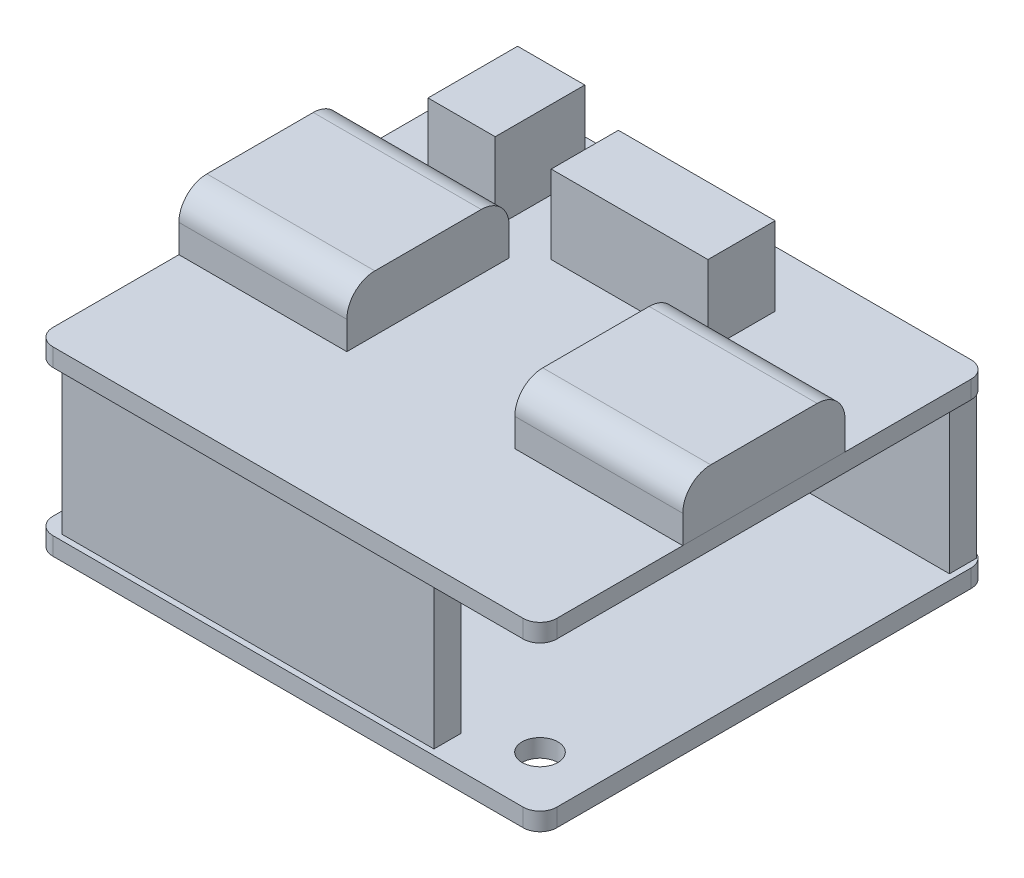
SolidWorks part; units mm, degrees
ref_plane "Front Plane" through (0, 0, 0) normal (0, 0, 1) x (1, 0, 0)
ref_plane "Top Plane" through (0, 0, 0) normal (0, 1, 0) x (1, 0, 0)
ref_plane "Right Plane" through (0, 0, 0) normal (1, 0, 0) x (0, 0, -1)
sketch "Sketch1" plane through (0, 0, 0) normal (0, 1, 0) x (1, 0, 0)
  line L1 (-22.5, -20) -> (22.5, -20)
  line L2 (-22.5, -20) -> (-22.5, 20)
  line L3 (-22.5, 20) -> (22.5, 20)
  line L4 (22.5, -20) -> (22.5, 20)
  line L5 (-22.5, -20) -> (22.5, 20) construction
  line L6 (-22.5, 20) -> (22.5, -20) construction
  point P0 (0, 0)
  dimension "D1" = 45
  dimension "D2" = 40
extrude "Boss-Extrude1" add sketch "Sketch1" along normal blind 1.6
sketch "Sketch2" plane through (0, 1.6, 0) normal (0, 1, 0) x (1, 0, 0)
  line L0 (-21.19, -20) -> (-21.19, 20) construction
  line L1 (21.99, 19.49) -> (-3.92, 19.49)
  line L2 (21.99, 19.49) -> (21.99, 17.08)
  line L3 (21.99, 17.08) -> (-3.92, 17.08)
  line L4 (-3.92, 19.49) -> (-3.92, 17.08)
  line L5 (12.52, -17.08) -> (-20.68, -17.08)
  line L6 (12.52, -17.08) -> (12.52, -19.49)
  line L7 (12.52, -19.49) -> (-20.68, -19.49)
  line L8 (-20.68, -17.08) -> (-20.68, -19.49)
  line L9 (-22.5, -20) -> (22.5, -20) construction
  line L10 (22.5, 20) -> (-22.5, 20) construction
  line L11 (22.5, -20) -> (22.5, 20) construction
  circle A0 centre (17.5, -15) radius 3.2 construction
  dimension "D6" = 6.4
  dimension "D1" = 2.41
  dimension "D2" = 2.41
  dimension "D3" = 33.2
  dimension "D4" = 25.91
  dimension "D5" = 43.69
  dimension "D7" = 5
  dimension "D8" = 5
  dimension "D9" = 0.51
  dimension "D10" = 0.51
  dimension "D11" = 0.51
  dimension "D12" = 0.51
extrude "Boss-Extrude2" add sketch "Sketch2" along normal blind 13
sketch "Sketch3" plane through (0, 14.6, 0) normal (0, 1, 0) x (1, 0, 0)
  line L0 (22.5, 20) -> (-22.5, 20) construction
  line L1 (22.5, -20) -> (-22.5, -20)
  line L2 (22.5, -20) -> (22.5, 20)
  line L3 (22.5, 20) -> (-22.5, 20)
  line L4 (-22.5, -20) -> (-22.5, 20)
  dimension "D1" = 45
extrude "Boss-Extrude3" add sketch "Sketch3" along normal blind 1.6
sketch "Sketch4" plane through (0, 16.2, 0) normal (0, 1, 0) x (1, 0, 0)
  line L0 (12.52, -17.08) -> (-20.68, -17.08)
  line L1 (12.52, -17.08) -> (12.52, -19.49)
  line L2 (12.52, -19.49) -> (-20.68, -19.49)
  line L3 (-20.68, -17.08) -> (-20.68, -19.49)
  line L4 (-22.5, -20) -> (22.5, -20) construction
  line L5 (22.5, -20) -> (22.5, 20) construction
  dimension "D1" = 0.51
  dimension "D2" = 2.41
  dimension "D3" = 33.2
  dimension "D4" = 9.98
extrude "Boss-Extrude4" [suppressed] add sketch "Sketch4" along normal blind 8.51
sketch "Sketch5" plane through (0, 16.2, 0) normal (0, 1, 0) x (1, 0, 0)
  line L0 (-22.5, 20) -> (-22.5, -20) construction
  line L1 (-22.5, -7.25) -> (-7.5, -7.25)
  line L2 (-22.5, -7.25) -> (-22.5, 7.25)
  line L3 (-22.5, 7.25) -> (-7.5, 7.25)
  line L4 (-7.5, -7.25) -> (-7.5, 7.25)
  line L5 (-0.88, 0) -> (0.88, 0) construction
  point P6 (-7.5, 0)
  dimension "D1" = 14.5
  dimension "D2" = 15
extrude "Boss-Extrude5" add sketch "Sketch5" along normal blind 5 separate body
fillet "Fillet1" radius 2.5 2 edges at (-15, 21.2, -7.25) (-15, 21.2, 7.25)
sketch "Sketch7" plane through (0, 1.6, 0) normal (0, 1, 0) x (1, 0, 0)
  line L0 (-22.5, -20) -> (22.5, -20) construction
  line L1 (22.5, -20) -> (22.5, 20) construction
  line L2 (-22.5, 20) -> (-22.5, -20) construction
  line L3 (22.5, 20) -> (-22.5, 20) construction
  circle A0 centre (17.5, -15) radius 1.6
  circle A1 centre (-17.5, 15) radius 1.6
  dimension "D3" = 3.2
  dimension "D6" = 3.2
  dimension "D1" = 5
  dimension "D2" = 5
  dimension "D4" = 5
  dimension "D5" = 5
extrude "Cut-Extrude1" cut sketch "Sketch7" against normal up to next (1.6 mm away)
fillet "Fillet2" radius 1.5 4 edges at (-22.5, 0.8, -20) (-22.5, 0.8, 20) (22.5, 0.8, 20) (22.5, 0.8, -20)
fillet "Fillet3" radius 1.5 4 edges at (-22.5, 15.4, -20) (22.5, 15.4, 20) (22.5, 15.4, -20) (-22.5, 15.4, 20)
sketch "Sketch8" plane through (0, 16.2, 0) normal (0, 1, 0) x (1, 0, 0)
  line L1 (-5.5, 9) -> (8.5, 9)
  line L2 (-5.5, 9) -> (-5.5, 15)
  line L3 (-5.5, 15) -> (8.5, 15)
  line L4 (8.5, 9) -> (8.5, 15)
  line L5 (21, 20) -> (-21, 20) construction
  line L6 (-22.5, 18.5) -> (-22.5, -18.5) construction
  line L7 (-16.5, 9) -> (-10.5, 9)
  line L8 (-16.5, 9) -> (-16.5, 17)
  line L9 (-16.5, 17) -> (-10.5, 17)
  line L10 (-10.5, 9) -> (-10.5, 17)
  dimension "D1" = 6
  dimension "D2" = 14
  dimension "D3" = 5
  dimension "D4" = 8
  dimension "D5" = 6
  dimension "D6" = 3
  dimension "D7" = 6
  dimension "D8" = 17
extrude "Boss-Extrude6" add sketch "Sketch8" along normal blind 7
pattern_linear "LPattern1" count 2 spacing 30 along (1, 0, 0) of "Boss-Extrude5"
